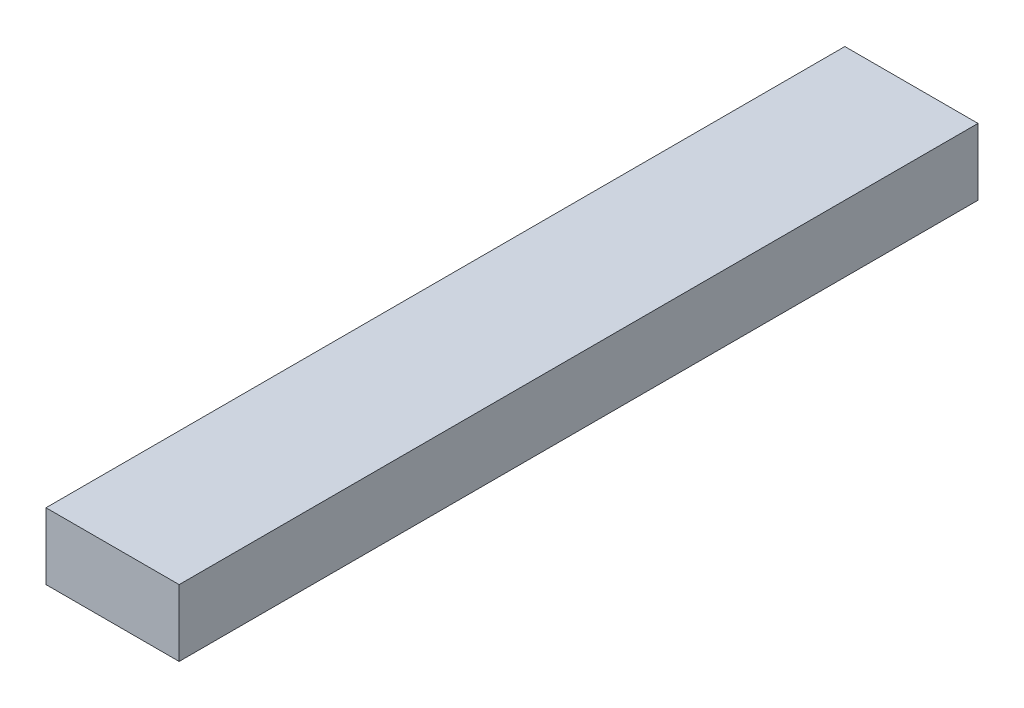
SolidWorks part; units mm, degrees
material "Beech"
ref_plane "Front Plane" through (0, 0, 0) normal (0, 0, 1) x (1, 0, 0)
ref_plane "Top Plane" through (0, 0, 0) normal (0, 1, 0) x (1, 0, 0)
ref_plane "Right Plane" through (0, 0, 0) normal (1, 0, 0) x (0, 0, -1)
sketch "Sketch1" plane through (0, 0, 0) normal (0, 1, 0) x (1, 0, 0)
  line L1 (0, 0) -> (304.8, 0)
  line L2 (0, 0) -> (0, 304.8)
  line L3 (0, 304.8) -> (304.8, 304.8)
  line L4 (304.8, 0) -> (304.8, 304.8)
  dimension "D1" = 304.8
  dimension "D2" = 304.8
extrude "Boss-Extrude1" add sketch "Sketch1" along normal blind 6.35
sketch "Sketch2" plane through (0, 6.35, 0) normal (0, 1, 0) x (1, 0, 0)
  line L1 (304.8, 304.8) -> (0, 304.8) construction
  line L2 (12.7, 304.8) -> (12.7, 228.6)
  line L3 (12.7, 228.6) -> (0, 228.6)
  line L4 (0, 304.8) -> (0, 0) construction
  line L6 (0, 228.6) -> (0, 0)
  line L7 (0, 0) -> (304.8, 0)
  line L8 (304.8, 0) -> (304.8, 304.8)
  line L9 (304.8, 304.8) -> (12.7, 304.8)
  dimension "D1" = 12.7
  dimension "D2" = 76.2
extrude "Cut-Extrude2" cut sketch "Sketch2" against normal blind 6.35 contours L3 L6 L7 L8 L9 L2
